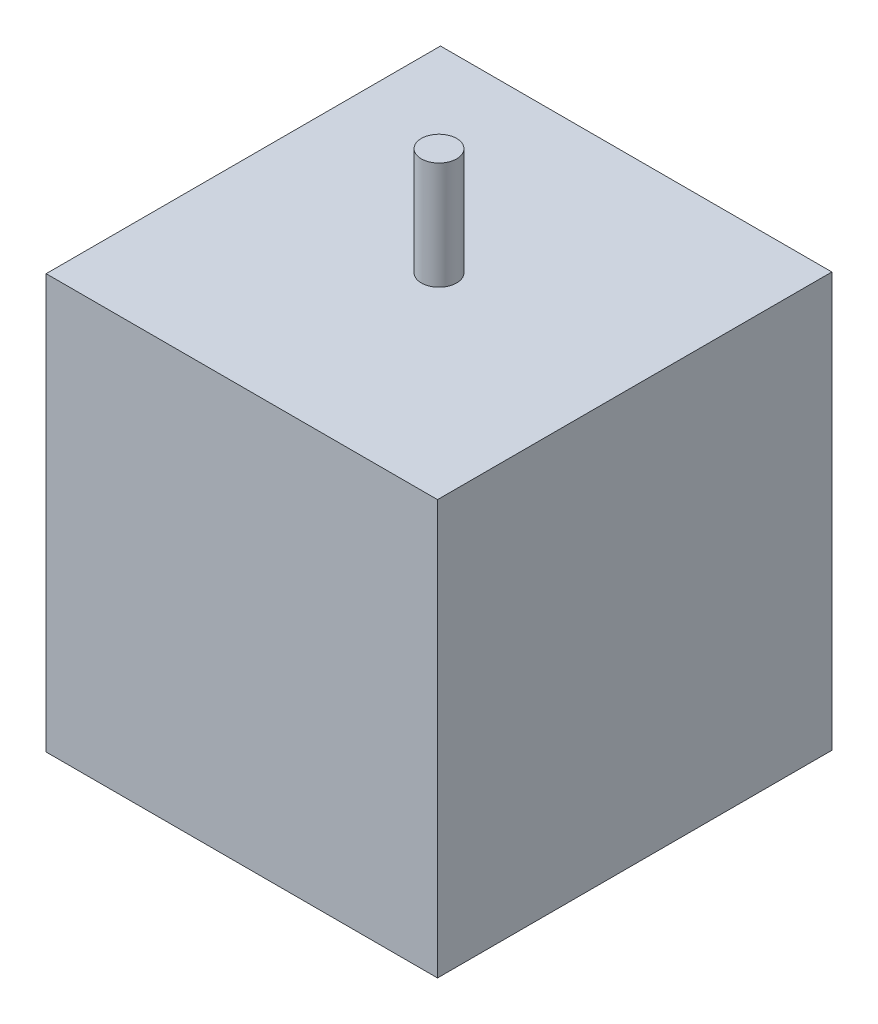
SolidWorks part; units mm, degrees
ref_plane "前视基准面" through (0, 0, 0) normal (0, 0, 1) x (1, 0, 0)
ref_plane "上视基准面" through (0, 0, 0) normal (0, 1, 0) x (1, 0, 0)
ref_plane "右视基准面" through (0, 0, 0) normal (1, 0, 0) x (0, 0, -1)
other "Configuration Table"
sketch "草图1" plane through (0, 0, 0) normal (0, 0, 1) x (1, 0, 0)
  line L1 (49.8504, 115.5602) -> (159.0235, 115.5602)
  line L2 (49.8504, 115.5602) -> (49.8504, 0)
  line L3 (49.8504, 0) -> (159.0235, 0)
  line L4 (159.0235, 115.5602) -> (159.0235, 0)
  arc A0 (57.9009, 117.9035) -> (42.9009, 102.9035) centre (57.9009, 102.9035) ccw construction
  point P5 (49.8504, 115.5602)
extrude "凸台-拉伸1" add sketch "草图1" along normal blind 110
sketch "草图2" plane through (0, 115.5602, 0) normal (0, 1, 0) x (1, 0, 0)
  circle A0 centre (104.437, -55) radius 4.9273
extrude "凸台-拉伸2" add sketch "草图2" against normal blind 140 and the other way blind 30
